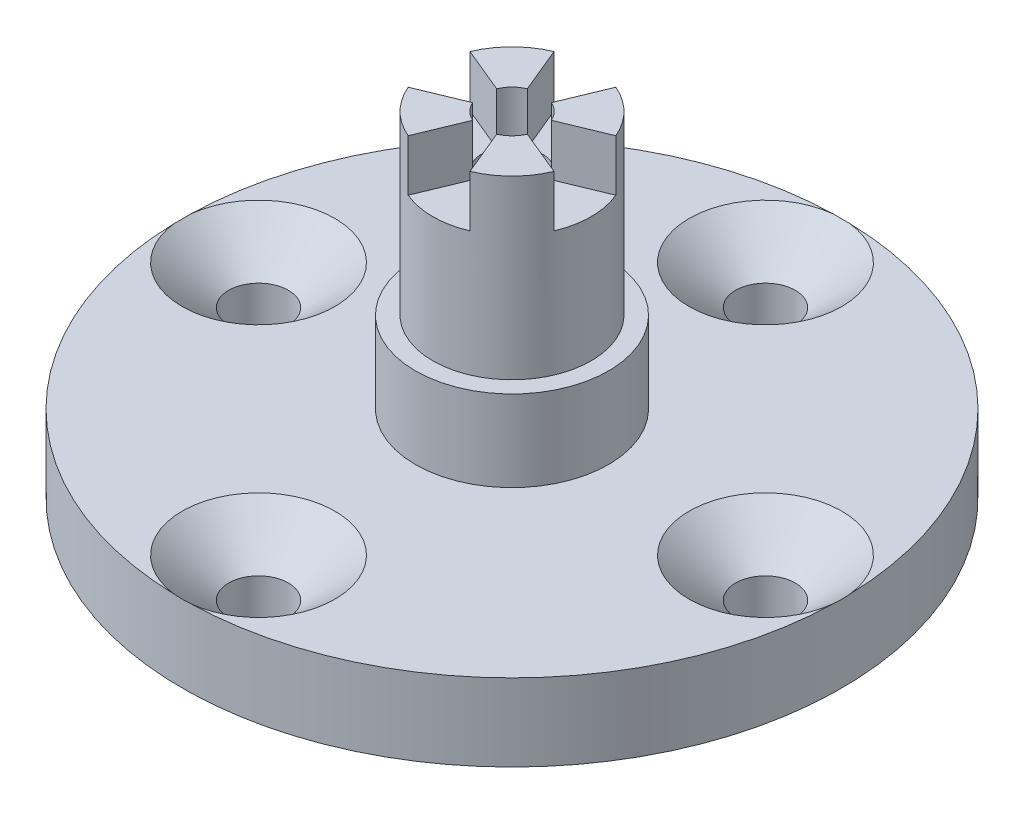
SolidWorks part; units mm, degrees
ref_plane "Front Plane" through (0, 0, 0) normal (0, 0, 1) x (1, 0, 0)
ref_plane "Top Plane" through (0, 0, 0) normal (0, 1, 0) x (1, 0, 0)
ref_plane "Right Plane" through (0, 0, 0) normal (1, 0, 0) x (0, 0, -1)
sketch "Sketch1" plane through (0, 0, 0) normal (0, 1, 0) x (1, 0, 0)
  circle A0 centre (0, 0) radius 4.7625
  dimension "D1" = 9.525
extrude "Boss-Extrude1" add sketch "Sketch1" along normal blind 10.16
sketch "Sketch3" plane through (0, 0, 0) normal (0, -1, 0) x (1, 0, 0)
  circle A9 centre (0, 0) radius 16.25
  dimension "D1" = 32.5
extrude "Boss-Extrude2" add sketch "Sketch3" along normal blind 3.81
hole_wizard "#4 Clearance Hole1" positions "Sketch4" profile "Sketch5" hole size "#4" standard "ANSI Inch" end condition through all
sketch "Sketch4" plane through (0, -3.81, 0) normal (0, -1, 0) x (-1, 0, 0)
  point P0 (0, 0)
sketch "Sketch5" plane through (0, -3.81, 0) normal (1, 0, 0) x (0, 0, -1)
  line L0 (0, 0) -> (0, 13.97)
  line L1 (0, 13.97) -> (1.4732, 13.97)
  line L2 (1.4732, 13.97) -> (1.4732, 0)
  line L5 (1.4732, 0) -> (0, 0)
  line L11 (0, -6.35) -> (0, 107.95) construction
  dimension "Thru Hole Dia." = 2.9464
  dimension "Thru Hole Depth" = 13.97
sketch "Sketch6" plane through (0, 10.16, 0) normal (0, 1, 0) x (1, 0, 0)
  circle A0 centre (0, 0) radius 3.9053
  circle A1 centre (0, 0) radius 4.7625
  circle A2 centre (0, 0) radius 4.7625 construction
  dimension "D1" = 7.8105
extrude "Cut-Extrude1" cut sketch "Sketch6" against normal blind 6.1595
sketch "Sketch7" plane through (0, -3.81, 0) normal (0, -1, 0) x (1, 0, 0)
  line L1 (-3.6662, 0) -> (-1.8331, -3.175)
  line L2 (-1.8331, -3.175) -> (1.8331, -3.175)
  line L3 (1.8331, -3.175) -> (3.6662, 0)
  line L4 (3.6662, 0) -> (1.8331, 3.175)
  line L5 (1.8331, 3.175) -> (-1.8331, 3.175)
  line L6 (-1.8331, 3.175) -> (-3.6662, 0)
  circle A0 centre (0, 0) radius 3.175 construction
  dimension "D1" = 6.35
extrude "Cut-Extrude4" cut sketch "Sketch7" against normal blind 6.35
sketch "Sketch8" plane through (0, 10.16, 0) normal (0, 1, 0) x (1, 0, 0)
  line L0 (0, 0) -> (-2.7614, 2.7614) construction
  line L1 (-0.593, 1.3486) -> (-1.5238, 3.5957)
  line L2 (-1.3486, 0.593) -> (-3.5957, 1.5238)
  line L3 (-1.4945, 3.608) -> (-0.5638, 1.3611) construction
  line L4 (0, 0) -> (0, 3.9053) construction
  line L6 (-1.3611, 0.5638) -> (-3.608, 1.4945) construction
  circle A0 centre (0, 0) radius 3.9053 construction
  circle A1 centre (0, 0) radius 1.4732 construction
  circle A2 centre (0, 0) radius 3.9053 construction
  arc A3 (-1.4945, 3.608) -> (-3.608, 1.4945) centre (0, 0) ccw construction
  arc A4 (-1.3611, 0.5638) -> (-0.5638, 1.3611) centre (0, 0) cw construction
  arc A5 (-3.5957, 1.5238) -> (-1.5238, 3.5957) centre (0, 0) cw
  arc A6 (-1.3486, 0.593) -> (-0.593, 1.3486) centre (0, 0) cw
  point P6 (-1.0417, 1.0417)
  dimension "D1" = 45
  dimension "D2" = 0.0635
  dimension "D3" = 45
extrude "Boss-Extrude3" add sketch "Sketch8" along normal blind 2.54
pattern_circular "CirPattern1" count 4 over 360 about axis through (0, 0, 0) along (0, 1, 0) of "Boss-Extrude3"
sketch "Sketch9" plane through (0, 0, 0) normal (0, 1, 0) x (1, 0, 0)
  line L0 (0, 0) -> (0, 12.5)
  dimension "D1" = 12.5
hole_wizard "CSK for #4 Flat Head Machine Screw (100)1" positions "Sketch10" profile "Sketch12" countersink size "#4" standard "ANSI Inch" end condition through all
sketch "Sketch10" plane through (0, 0, 0) normal (0, 1, 0) x (1, 0, 0)
  point P0 (0, 12.5)
sketch "Sketch12" plane through (0, 0, -12.5) normal (1, 0, 0) x (0, 0, 1)
  line L0 (0, 0) -> (0, 3.81)
  line L1 (0, 3.81) -> (1.4732, 3.81)
  line L2 (1.4732, 3.81) -> (1.4732, 1.9236)
  line L3 (1.4732, 1.9236) -> (3.7656, 0)
  line L5 (3.7656, 0) -> (0, 0)
  line L6 (-1.4732, 1.9236) -> (-3.7656, 0) construction
  line L11 (0, -6.35) -> (0, 107.95) construction
  dimension "Thru Hole Dia." = 2.9464
  dimension "Thru Hole Depth" = 3.81
  dimension "Near C'Sink Dia." = 7.5312
  dimension "Near C'Sink Angle" = 100
pattern_circular "CirPattern2" count 4 over 360 about axis through (0, 0, 0) along (0, 1, 0) of "CSK for #4 Flat Head Machine Screw (100)1"
